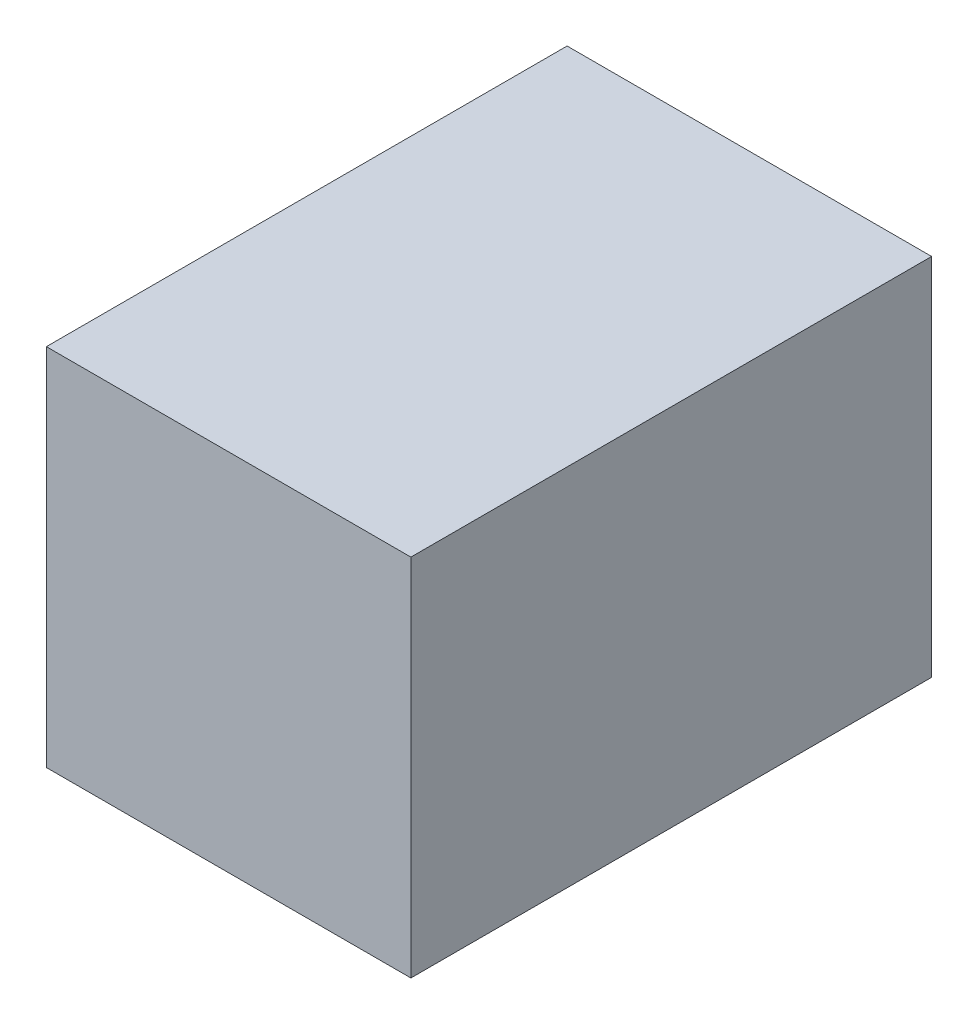
SolidWorks part; units mm, degrees
ref_plane "Plan de face" through (0, 0, 0) normal (0, 0, 1) x (1, 0, 0)
ref_plane "Plan de dessus" through (0, 0, 0) normal (0, 1, 0) x (1, 0, 0)
ref_plane "Plan de droite" through (0, 0, 0) normal (1, 0, 0) x (0, 0, -1)
sketch "Esquisse1" plane through (0, 0, 0) normal (0, 0, 1) x (1, 0, 0)
  line L1 (-17.5, 17.5) -> (17.5, 17.5)
  line L2 (-17.5, 17.5) -> (-17.5, -17.5)
  line L3 (-17.5, -17.5) -> (17.5, -17.5)
  line L4 (17.5, 17.5) -> (17.5, -17.5)
  line L5 (-17.5, 17.5) -> (17.5, -17.5) construction
  line L6 (-17.5, -17.5) -> (17.5, 17.5) construction
  point P0 (0, 0)
  dimension "D1" = 35
extrude "Boss.-Extru.1" add sketch "Esquisse1" along normal blind 50
sketch "Esquisse2" plane through (0, 0, 0) normal (0, 0, -1) x (-1, 0, 0)
  line L1 (-15, 15) -> (15, 15)
  line L2 (-15, 15) -> (-15, -15)
  line L3 (-15, -15) -> (15, -15)
  line L4 (15, 15) -> (15, -15)
  line L5 (-15, 15) -> (15, -15) construction
  line L6 (-15, -15) -> (15, 15) construction
  point P0 (0, 0)
  dimension "D1" = 30
extrude "Enlèv. mat.-Extru.1" cut sketch "Esquisse2" against normal blind 45
